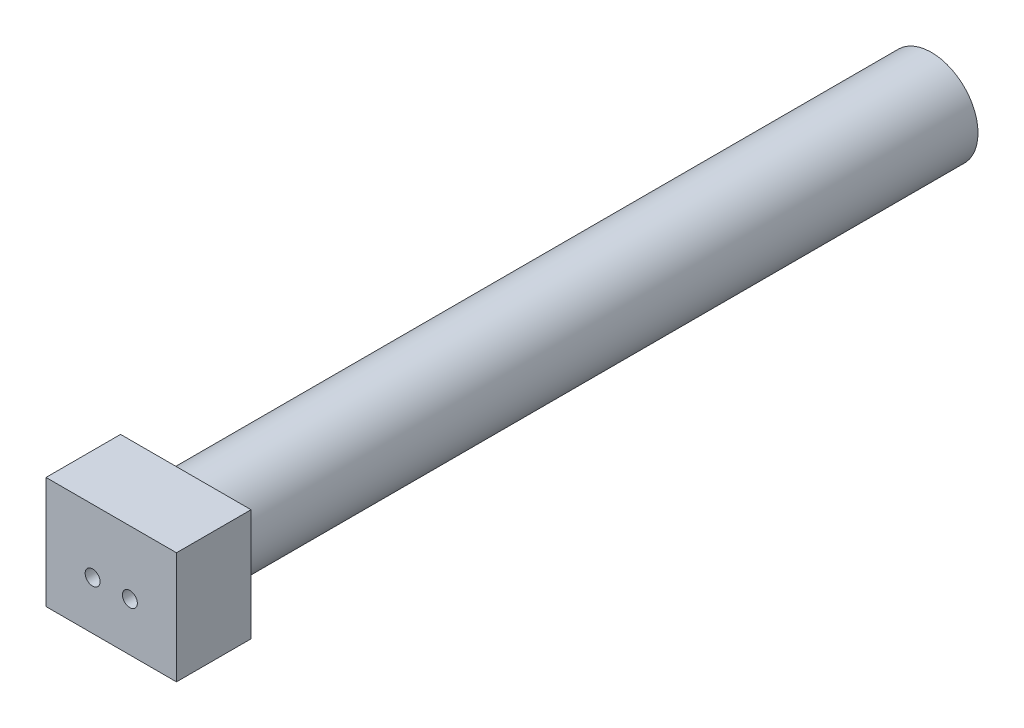
SolidWorks part; units mm, degrees
ref_plane "Front" through (0, 0, 0) normal (0, 0, 1) x (1, 0, 0)
ref_plane "Top" through (0, 0, 0) normal (0, 1, 0) x (1, 0, 0)
ref_plane "Right" through (0, 0, 0) normal (1, 0, 0) x (0, 0, -1)
sketch "Esquisse1" plane through (0, 0, 0) normal (0, 0, 1) x (1, 0, 0)
  circle A0 centre (0, 0) radius 8
  circle A1 centre (0, 0) radius 12.5
  dimension "D1" = 16
  dimension "D2" = 25
extrude "Boss.-Extru.1" add sketch "Esquisse1" along normal blind 200
sketch "Esquisse2" plane through (0, 0, 200) normal (0, 0, 1) x (1, 0, 0)
  line L1 (-17.5, 15) -> (17.5, 15)
  line L2 (-17.5, 15) -> (-17.5, -15)
  line L3 (-17.5, -15) -> (17.5, -15)
  line L4 (17.5, 15) -> (17.5, -15)
  circle A1 centre (0, 0) radius 8 construction
  dimension "D1" = 30
  dimension "D2" = 35
  dimension "D3" = 15
  dimension "D4" = 17.5
extrude "Boss.-Extru.2" add sketch "Esquisse2" along normal blind 20
sketch "Esquisse3" plane through (0, 0, 220) normal (0, 0, 1) x (1, 0, 0)
  line L0 (0, 15) -> (0, -15) construction
  line L1 (17.5, 15) -> (-17.5, 15) construction
  line L2 (-17.5, -15) -> (17.5, -15) construction
  circle A0 centre (5, -2) radius 2
  circle A1 centre (-5, -2) radius 2
  dimension "D1" = 4
  dimension "D2" = 10
  dimension "D3" = 5
  dimension "D4" = 13
extrude "Enlèv. mat.-Extru.1" cut sketch "Esquisse3" against normal blind 20
